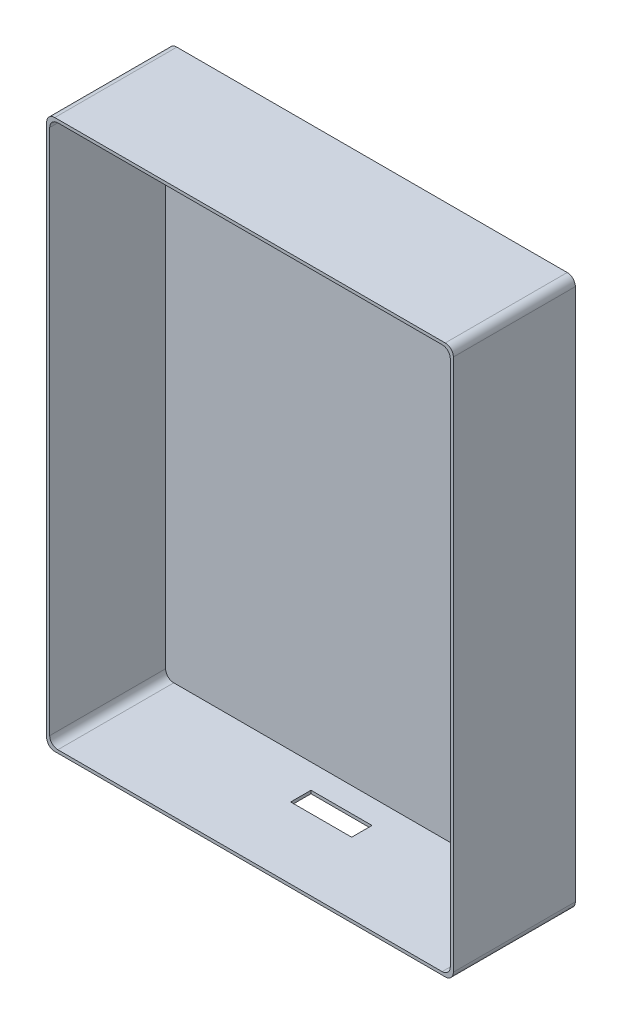
SolidWorks part; units mm, degrees
ref_plane "Front Plane" through (0, 0, 0) normal (0, 0, 1) x (1, 0, 0)
ref_plane "Top Plane" through (0, 0, 0) normal (0, 1, 0) x (1, 0, 0)
ref_plane "Right Plane" through (0, 0, 0) normal (1, 0, 0) x (0, 0, -1)
sketch "Sketch1" plane through (0, 0, 0) normal (0, 0, 1) x (1, 0, 0)
  line L1 (-50, 67.5) -> (50, 67.5)
  line L2 (-50, 67.5) -> (-50, -67.5)
  line L3 (-50, -67.5) -> (50, -67.5)
  line L4 (50, 67.5) -> (50, -67.5)
  line L5 (-50, 67.5) -> (50, -67.5) construction
  line L6 (-50, -67.5) -> (50, 67.5) construction
  point P0 (0, 0)
  dimension "D1" = 135
  dimension "D2" = 100
extrude "Boss-Extrude1" add sketch "Sketch1" along normal blind 30
sketch "Sketch2" plane through (0, 0, 30) normal (0, 0, 1) x (1, 0, 0)
  line L1 (-49.25, 66.75) -> (49.25, 66.75)
  line L2 (-49.25, 66.75) -> (-49.25, -66.75)
  line L3 (-49.25, -66.75) -> (49.25, -66.75)
  line L4 (49.25, 66.75) -> (49.25, -66.75)
  line L5 (0, -66.75) -> (0, 66.75) construction
  line L6 (-49.25, 0) -> (49.25, 0) construction
  line L7 (-49.25, 66.75) -> (49.25, 66.75)
  line L8 (-49.25, 66.75) -> (-49.25, -66.75)
  line L9 (-49.25, -66.75) -> (49.25, -66.75)
  line L10 (49.25, 66.75) -> (49.25, -66.75)
  line L11 (0, -66.75) -> (0, 66.75) construction
  line L12 (-49.25, 0) -> (49.25, 0) construction
  point P0 (0, 0)
  point P4 (0, 0)
  dimension "D1" = 133.5
  dimension "D2" = 98.5
extrude "Cut-Extrude1" cut sketch "Sketch2" against normal blind 28.5 contours L4 L1 L2 L3
fillet "Fillet21" radius 2 4 edges at (-50, -67.5, 15) (-50, 67.5, 15) (50, 67.5, 15) (50, -67.5, 15)
fillet "Fillet22" radius 2 4 edges at (-49.25, 66.75, 15.75) (-49.25, -66.75, 15.75) (49.25, -66.75, 15.75) (49.25, 66.75, 15.75)
sketch "Sketch4" plane through (0, -67.5, 0) normal (0, -1, 0) x (1, 0, 0)
  line L0 (0, 0) -> (0, 30)
  line L1 (-48, 30) -> (48, 30) construction
  line L2 (0, 0) -> (0, 10)
  line L4 (-7.5, 12.5) -> (7.5, 12.5)
  line L5 (-7.5, 12.5) -> (-7.5, 7.5)
  line L6 (-7.5, 7.5) -> (7.5, 7.5)
  line L7 (7.5, 12.5) -> (7.5, 7.5)
  line L8 (-7.5, 12.5) -> (7.5, 7.5) construction
  line L9 (-7.5, 7.5) -> (7.5, 12.5) construction
  dimension "D1" = 10
  dimension "D2" = 5
  dimension "D3" = 15
extrude "Cut-Extrude2" cut sketch "Sketch4" against normal blind 1.5 contours L7 L4 L0 L2 L6 | L5 L6 L2 L0 L4
